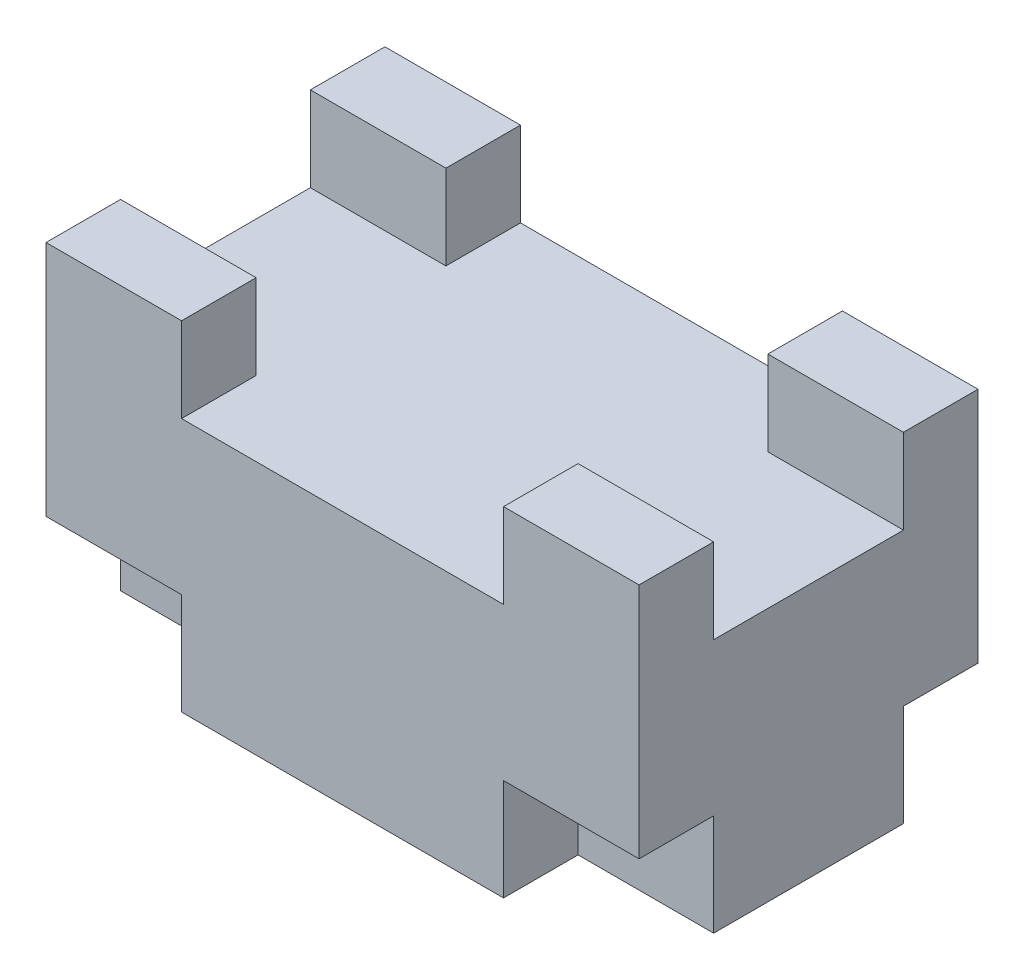
SolidWorks part; units mm, degrees
ref_plane "Front Plane" through (0, 0, 0) normal (0, 0, 1) x (1, 0, 0)
ref_plane "Top Plane" through (0, 0, 0) normal (0, 1, 0) x (1, 0, 0)
ref_plane "Right Plane" through (0, 0, 0) normal (1, 0, 0) x (0, 0, -1)
sketch "Sketch2" plane through (0, 0, 0) normal (0, 1, 0) x (1, 0, 0)
  line L1 (-87.5, 50) -> (87.5, 50)
  line L2 (-87.5, 50) -> (-87.5, -50)
  line L3 (-87.5, -50) -> (87.5, -50)
  line L4 (87.5, 50) -> (87.5, -50)
  line L5 (-87.5, 50) -> (87.5, -50) construction
  line L6 (-87.5, -50) -> (87.5, 50) construction
  point P0 (0, 0)
  dimension "D1" = 175
  dimension "D2" = 100
extrude "Boss-Extrude1" add sketch "Sketch2" along normal blind 75
sketch "Sketch3" plane through (0, 0, 0) normal (0, -1, 0) x (1, 0, 0)
  line L1 (-87.5, 50) -> (-47.5, 50)
  line L2 (-87.5, 50) -> (-87.5, 28)
  line L3 (-87.5, 28) -> (-47.5, 28)
  line L4 (-47.5, 50) -> (-47.5, 28)
  line L5 (87.5, 50) -> (47.5, 50)
  line L6 (87.5, 50) -> (87.5, 28)
  line L7 (87.5, 28) -> (47.5, 28)
  line L8 (47.5, 50) -> (47.5, 28)
  line L9 (-87.5, -50) -> (-47.5, -50)
  line L10 (-87.5, -50) -> (-87.5, -28)
  line L11 (-87.5, -28) -> (-47.5, -28)
  line L12 (-47.5, -50) -> (-47.5, -28)
  line L13 (87.5, -50) -> (47.5, -50)
  line L14 (87.5, -50) -> (87.5, -28)
  line L15 (87.5, -28) -> (47.5, -28)
  line L16 (47.5, -50) -> (47.5, -28)
  dimension "D1" = 22
  dimension "D2" = 40
  dimension "D3" = 22
  dimension "D4" = 40
  dimension "D5" = 40
  dimension "D6" = 22
  dimension "D7" = 40
  dimension "D8" = 22
extrude "Cut-Extrude1" cut sketch "Sketch3" against normal blind 30
sketch "Sketch4" plane through (0, 75, 0) normal (0, 1, 0) x (1, 0, 0)
  line L0 (-87.5, -50) -> (87.5, -50) construction
  line L1 (-87.5, 50) -> (-47.5, 50)
  line L2 (-87.5, 50) -> (-87.5, 28)
  line L3 (-87.5, 28) -> (-47.5, 28)
  line L4 (-47.5, 50) -> (-47.5, 28)
  line L5 (87.5, 50) -> (47.5, 50)
  line L6 (87.5, 50) -> (87.5, 28)
  line L7 (87.5, 28) -> (47.5, 28)
  line L8 (47.5, 50) -> (47.5, 28)
  line L9 (87.5, -50) -> (47.5, -50)
  line L10 (87.5, -50) -> (87.5, -28)
  line L11 (87.5, -28) -> (47.5, -28)
  line L12 (47.5, -50) -> (47.5, -28)
  line L13 (-87.5, -50) -> (-47.5, -50)
  line L14 (-87.5, -50) -> (-87.5, -28)
  line L15 (-87.5, -28) -> (-47.5, -28)
  line L16 (-47.5, -50) -> (-47.5, -28)
  line L17 (-87.5, 50) -> (-87.5, -50) construction
  dimension "D1" = 40
  dimension "D2" = 22
  dimension "D3" = 40
  dimension "D4" = 22
  dimension "D5" = 40
  dimension "D6" = 22
  dimension "D7" = 40
  dimension "D8" = 22
extrude "Boss-Extrude2" add sketch "Sketch4" along normal blind 25
